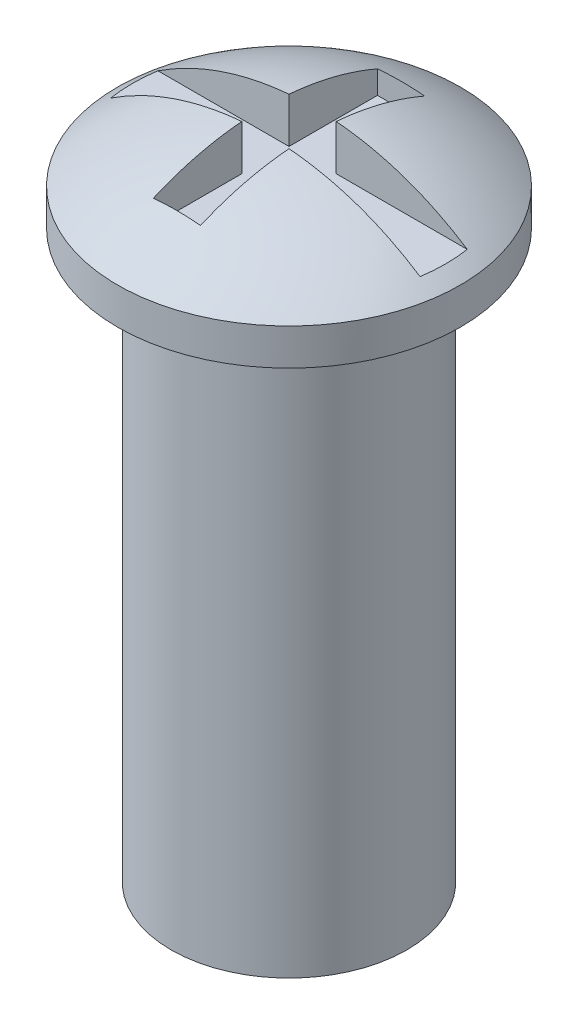
SolidWorks part; units mm, degrees
ref_plane "前视基准面" through (0, 0, 0) normal (0, 0, 1) x (1, 0, 0)
ref_plane "上视基准面" through (0, 0, 0) normal (0, 1, 0) x (1, 0, 0)
ref_plane "右视基准面" through (0, 0, 0) normal (1, 0, 0) x (0, 0, -1)
sketch "草图1" plane through (0, 0, 0) normal (0, 1, 0) x (1, 0, 0)
  circle A0 centre (0, 0) radius 2.5
  dimension "D1" = 5
extrude "拉伸1" add sketch "草图1" along normal blind 12
sketch "草图2" plane through (0, 12, 0) normal (0, 1, 0) x (-1, 0, 0)
  circle A0 centre (0, 0) radius 3.635
  dimension "D1" = 7.27
extrude "拉伸2" add sketch "草图2" along normal blind 2
sketch "草图3" plane through (0, 14, 0) normal (0, 1, 0) x (-1, 0, 0)
  line L0 (4.0624, 0) -> (-4.2778, 0) construction
  line L1 (0, -3.5166) -> (0, 3.738) construction
  line L3 (5.386, -0.5) -> (-5.386, -0.5)
  line L4 (5.386, -0.5) -> (5.386, 0.5)
  line L5 (5.386, 0.5) -> (-5.386, 0.5)
  line L6 (-5.386, -0.5) -> (-5.386, 0.5)
  dimension "D1" = 1
extrude "切除-拉伸1" cut sketch "草图3" against normal blind 1
sketch "草图4" plane through (0, 14, 0) normal (0, 1, 0) x (-1, 0, 0)
  line L0 (0, -3.8639) -> (0, 3.6765) construction
  line L1 (1.7727, 0) -> (-1.7019, 0) construction
  line L2 (0.5, -2.375) -> (-0.5, -2.375)
  line L3 (0.5, -2.375) -> (0.5, 2.375)
  line L4 (0.5, 2.375) -> (-0.5, 2.375)
  line L5 (-0.5, -2.375) -> (-0.5, 2.375)
  dimension "D1" = 1
  dimension "D2" = 4.75
extrude "切除-拉伸2" cut sketch "草图4" against normal blind 1
sketch "草图5" plane through (0, 0, 0) normal (1, 0, 0) x (0, 0, -1)
  line L0 (0, -2.1059) -> (0, 12.2815) construction
  line L1 (-0.5, 14) -> (-3.635, 14) construction
  line L2 (0, 14.6534) -> (-4.2277, 14.6534)
  line L3 (-4.2277, 12.2575) -> (-4.2277, 14.6534)
  line L5 (0, 14.6534) -> (0, 14)
  arc A2 (0, 14) -> (-4.2277, 12.2575) centre (0, 8) ccw
  dimension "D1" = 6
revolve "切除-旋转16" cut sketch "草图5" angle 360 about L0
